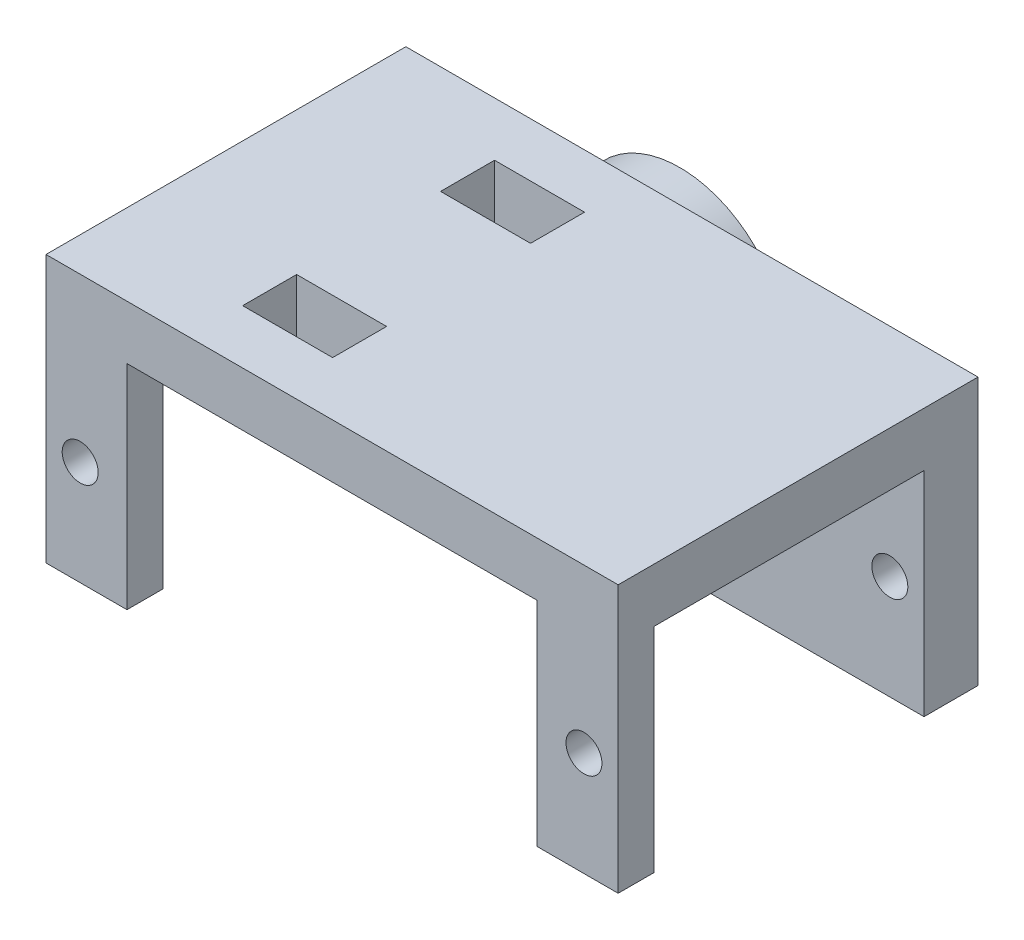
SolidWorks part; units mm, degrees
ref_plane "Front Plane" through (0, 0, 0) normal (0, 0, 1) x (1, 0, 0)
ref_plane "Top Plane" through (0, 0, 0) normal (0, 1, 0) x (1, 0, 0)
ref_plane "Right Plane" through (0, 0, 0) normal (1, 0, 0) x (0, 0, -1)
sketch "Sketch1" plane through (0, 0, 0) normal (0, 0, 1) x (1, 0, 0)
  line L1 (15.9, -6.625) -> (-15.9, -6.625)
  line L2 (15.9, -6.625) -> (15.9, 6.625)
  line L3 (15.9, 6.625) -> (-15.9, 6.625)
  line L4 (-15.9, -6.625) -> (-15.9, 6.625)
  line L5 (15.9, -6.625) -> (-15.9, 6.625) construction
  line L6 (15.9, 6.625) -> (-15.9, -6.625) construction
  point P0 (0, 0)
  dimension "D1" = 31.8
  dimension "D2" = 13.25
extrude "Boss-Extrude3" add sketch "Sketch1" along normal blind 3
sketch "Sketch3" plane through (0, 0, 3) normal (0, 0, 1) x (1, 0, 0)
  line L1 (-15.9, 6.625) -> (15.9, 6.625)
  line L2 (-15.9, 6.625) -> (-15.9, 9.625)
  line L3 (-15.9, 9.625) -> (15.9, 9.625)
  line L4 (15.9, 6.625) -> (15.9, 9.625)
  dimension "D1" = 3
  dimension "D2" = 31.8
extrude "Boss-Extrude4" add sketch "Sketch3" against normal blind 24
sketch "Sketch4" plane through (0, 0, 3) normal (0, 0, 1) x (1, 0, 0)
  line L0 (0, 9.625) -> (0, 6.625)
  line L1 (15.9, 9.625) -> (-15.9, 9.625) construction
  line L2 (-15.9, 9.625) -> (-15.9, -6.625) construction
  line L3 (11.4, -6.625) -> (-11.4, -6.625)
  line L4 (11.4, -6.625) -> (11.4, 6.625)
  line L5 (11.4, 6.625) -> (-11.4, 6.625)
  line L6 (-11.4, -6.625) -> (-11.4, 6.625)
  line L7 (11.4, -6.625) -> (-11.4, 6.625) construction
  line L8 (11.4, 6.625) -> (-11.4, -6.625) construction
  line L9 (-15.9, -6.625) -> (15.9, -6.625) construction
  point P5 (0, 0)
  dimension "D1" = 3
  dimension "D2" = 4.5
  dimension "D3" = 0
extrude "Cut-Extrude3" cut sketch "Sketch4" against normal blind 3 contours L6 L4 L5
sketch "Sketch6" plane through (0, 6.625, 0) normal (0, -1, 0) x (1, 0, 0)
  line L0 (15.9, 3) -> (15.9, -15.4)
  line L1 (15.9, -21) -> (15.9, 0) construction
  line L2 (-15.9, -21) -> (-15.9, 0) construction
  line L3 (15.9, -15.4) -> (-15.9, -15.4)
  line L4 (15.9, -15.4) -> (15.9, -17.4)
  line L5 (15.9, -17.4) -> (-15.9, -17.4)
  line L6 (-15.9, -15.4) -> (-15.9, -17.4)
  line M3 (15.9, -21) -> (15.9, 0)
  line M9 (-15.9, 0) -> (-15.9, -21)
  dimension "D1" = 18.4
  dimension "D2" = 2
extrude "Boss-Extrude5" add sketch "Sketch6" along normal up to surface (13.25 mm away) contours L5 L3 M3 M9 up to face at (-13.65, -6.625, 1.5)
sketch "Sketch7" plane through (-15.9, 0, 0) normal (-1, 0, 0) x (0, 0, 1)
  line L1 (-21, 9.625) -> (-17.4, 9.625)
  line L2 (-21, 9.625) -> (-21, 6.625)
  line L3 (-21, 6.625) -> (-17.4, 6.625)
  line L4 (-17.4, 9.625) -> (-17.4, 6.625)
extrude "Cut-Extrude4" cut sketch "Sketch7" against normal through all
sketch "Sketch8" plane through (15.9, 0, 0) normal (1, 0, 0) x (0, 0, -1)
  line L1 (15.4, -6.625) -> (17.4, -6.625)
  line L2 (15.4, -6.625) -> (15.4, -7.875)
  line L3 (15.4, -7.875) -> (17.4, -7.875)
  line L4 (17.4, -6.625) -> (17.4, -7.875)
  dimension "D1" = 1.25
extrude "Boss-Extrude6" add sketch "Sketch8" against normal up to surface (31.8 mm away) up to face at (-15.9, 0.75, -7.45)
sketch "Sketch10" plane through (15.9, 0, 0) normal (1, 0, 0) x (0, 0, -1)
  line L1 (17.4, 9.625) -> (15.4, 9.625)
  line L2 (17.4, 9.625) -> (17.4, -7.875)
  line L3 (17.4, -7.875) -> (15.4, -7.875)
  line L4 (15.4, 9.625) -> (15.4, -7.875)
extrude "Cut-Extrude6" cut sketch "Sketch10" against normal through all
sketch "Sketch11" plane through (15.9, 0, 0) normal (1, 0, 0) x (0, 0, -1)
  line L1 (-3, -6.625) -> (0, -6.625)
  line L2 (-3, -6.625) -> (-3, -7.875)
  line L3 (-3, -7.875) -> (0, -7.875)
  line L4 (0, -6.625) -> (0, -7.875)
  dimension "D1" = 1.25
extrude "Boss-Extrude7" add sketch "Sketch11" against normal up to surface (27.3 mm away)
ref_plane "Plane7" through (0, 0, 0) normal (1, 0, 0) x (0, 0, -1)
mirror "Mirror2" about plane through (0, 0, 0) normal (1, 0, 0) of "Boss-Extrude7"
sketch "Sketch12" plane through (0, 0, 3) normal (0, 0, 1) x (1, 0, 0)
  line L0 (-15.9, -7.875) -> (15.9, -7.875) construction
  line L1 (-11.4, -6.625) -> (11.4, -6.625)
  line L2 (-11.4, -6.625) -> (-11.4, -7.875)
  line L3 (-11.4, -7.875) -> (11.4, -7.875)
  line L4 (11.4, -6.625) -> (11.4, -7.875)
extrude "Cut-Extrude7" cut sketch "Sketch12" against normal blind 4
sketch "Sketch15" plane through (0, 9.625, 0) normal (0, 1, 0) x (1, 0, 0)
  line L0 (15.9, 15.4) -> (15.9, -3) construction
  line L1 (-15.9, 15.4) -> (15.9, 15.4)
  line L2 (-15.9, 15.4) -> (-15.9, 18.4)
  line L3 (-15.9, 18.4) -> (15.9, 18.4)
  line L4 (15.9, 15.4) -> (15.9, 18.4)
  dimension "D1" = 3
extrude "Boss-Extrude9" add sketch "Sketch15" against normal up to surface (17.5 mm away) up to face at (13.65, -7.875, 1.5)
sketch "Sketch19" plane through (0, 0, 3) normal (0, 0, 1) x (1, 0, 0)
  line L0 (-15.9, 9.625) -> (15.9, 9.625)
  line L1 (15.9, 9.625) -> (15.9, -7.875)
  line L2 (15.9, -7.875) -> (11.4, -7.875)
  line L3 (11.4, -7.875) -> (11.4, 6.625)
  line L4 (11.4, 6.625) -> (-11.4, 6.625)
  line L5 (-11.4, 6.625) -> (-11.4, -7.875)
  line L6 (-11.4, -7.875) -> (-15.9, -7.875)
  line L7 (-15.9, -7.875) -> (-15.9, 9.625)
extrude "Boss-Extrude12" add sketch "Sketch19" against normal blind 5
sketch "Sketch20" plane through (-15.9, 0, 0) normal (-1, 0, 0) x (0, 0, 1)
  line L0 (-2, -7.875) -> (3, -7.875) construction
  line L1 (-15.4, 6.625) -> (-0.4, 6.625)
  line L2 (-15.4, 6.625) -> (-15.4, -7.875)
  line L3 (-15.4, -7.875) -> (-0.4, -7.875)
  line L4 (-0.4, 6.625) -> (-0.4, -7.875)
  line L5 (-18.4, 9.625) -> (3, 9.625) construction
  line L6 (1.6, 9.625) -> (6.8306, 9.625)
  line L7 (1.6, 9.625) -> (1.6, -7.875)
  line L8 (1.6, -7.875) -> (6.8306, -7.875)
  line L9 (6.8306, 9.625) -> (6.8306, -7.875)
  dimension "D1" = 15
  dimension "D2" = 17
extrude "Cut-Extrude9" cut sketch "Sketch20" against normal blind 100
sketch "Sketch22" plane through (0, 0, 1.6) normal (0, 0, 1) x (1, 0, 0)
  line L0 (15.9, 9.625) -> (15.9, -7.875) construction
  line L1 (-15.9, -7.875) -> (15.9, -7.875)
  line L2 (-15.9, -7.875) -> (-15.9, -5.225)
  line L3 (-15.9, -5.225) -> (15.9, -5.225)
  line L4 (15.9, -7.875) -> (15.9, -5.225)
  line L6 (15.9, 6.625) -> (-15.9, 6.625) construction
  line L7 (0, -1.1) -> (0, 1.1) construction
  circle A0 centre (-14, 0.575) radius 1
  circle A1 centre (14, 0.575) radius 1
  dimension "D2" = 14
  dimension "D4" = 2
  dimension "D1" = 11.85
  dimension "D3" = 5.8
extrude "Cut-Extrude11" cut sketch "Sketch22" against normal blind 20
sketch "Sketch24" plane through (0, 0, -18.4) normal (0, 0, -1) x (-1, 0, 0)
  line L0 (-15.9, -5.225) -> (15.9, -5.225) construction
  line L1 (11.4, 6.625) -> (11.4, -5.225) construction
  circle A0 centre (5.47, 0.7) radius 5.925
  dimension "D1" = 5.925
  dimension "D2" = 11.85
  dimension "D3" = 5.93
extrude "Boss-Extrude13" add sketch "Sketch24" along normal blind 4.8
sketch "Sketch25" plane through (0, 0, -23.2) normal (0, 0, -1) x (-1, 0, 0)
  circle A0 centre (5.47, 0.7) radius 2.5
  dimension "D1" = 5
extrude "Boss-Extrude14" add sketch "Sketch25" along normal blind 2
sketch "Sketch27" plane through (0, 6.625, 0) normal (0, -1, 0) x (1, 0, 0)
  line L0 (15.9, -15.4) -> (-15.9, -15.4) construction
  line L1 (-7.97, -15.4) -> (-2.97, -15.4)
  line L2 (-7.97, -15.4) -> (-7.97, -12.4)
  line L3 (-7.97, -12.4) -> (-2.97, -12.4)
  line L4 (-2.97, -15.4) -> (-2.97, -12.4)
  line L5 (-7.97, -15.4) -> (-2.97, -12.4) construction
  line L6 (-7.97, -12.4) -> (-2.97, -15.4) construction
  line L7 (-15.9, -15.4) -> (-15.9, -0.4) construction
  line L8 (-7.97, -4.4) -> (-2.97, -4.4)
  line L9 (-7.97, -4.4) -> (-7.97, -1.4)
  line L10 (-7.97, -1.4) -> (-2.97, -1.4)
  line L11 (-2.97, -4.4) -> (-2.97, -1.4)
  line L12 (-7.97, -4.4) -> (-2.97, -1.4) construction
  line L13 (-7.97, -1.4) -> (-2.97, -4.4) construction
  point P0 (-5.47, -13.9)
  point P7 (-5.47, -2.9)
  dimension "D1" = 5
  dimension "D2" = 3
  dimension "D3" = 0
  dimension "D4" = 12.5
extrude "Cut-Extrude12" cut sketch "Sketch27" against normal blind 10
